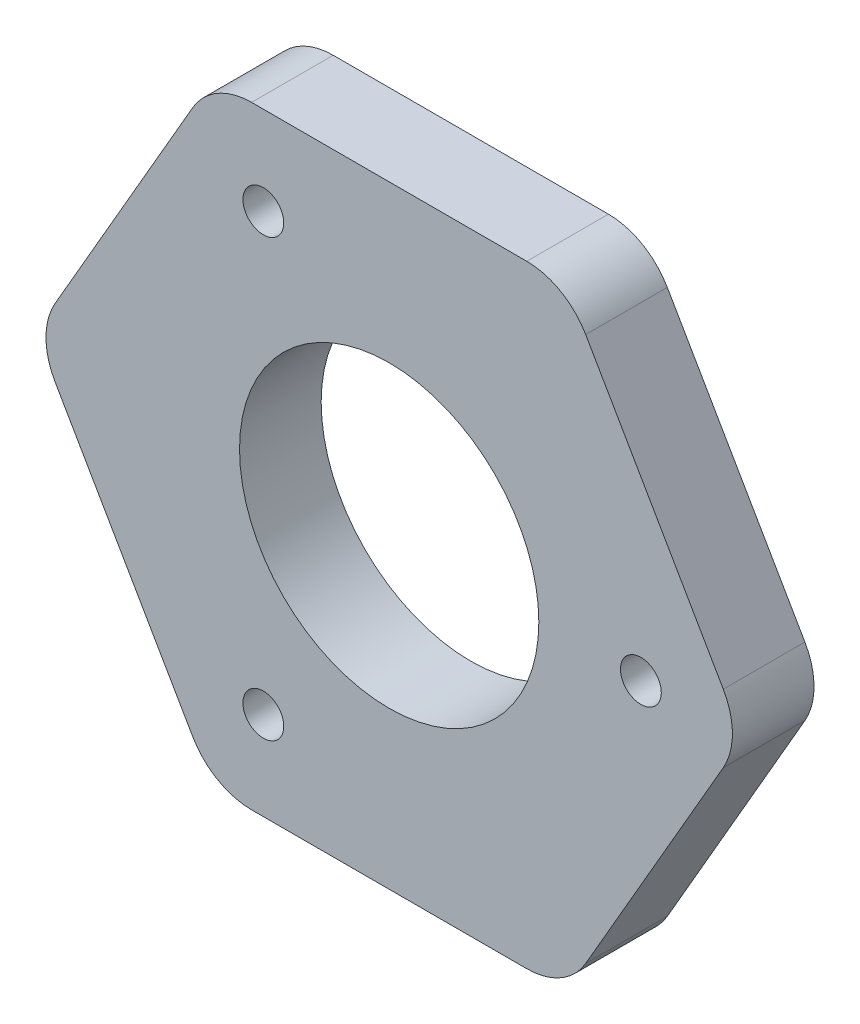
SolidWorks part; units mm, degrees
ref_plane "Front Plane" through (0, 0, 0) normal (0, 0, 1) x (1, 0, 0)
ref_plane "Top Plane" through (0, 0, 0) normal (0, 1, 0) x (1, 0, 0)
ref_plane "Right Plane" through (0, 0, 0) normal (1, 0, 0) x (0, 0, -1)
sketch "Sketch1" plane through (0, 0, 0) normal (0, 0, 1) x (1, 0, 0)
  line L6 (-32.5443, 48.7733) -> (-22.4311, 66.29)
  line L7 (-22.4311, 71.29) -> (-32.5443, 88.8067)
  line L8 (-36.8745, 91.3067) -> (-57.101, 91.3067)
  line L9 (-61.4311, 88.8067) -> (-71.5443, 71.29)
  line L10 (-71.5443, 66.29) -> (-61.4311, 48.7733)
  line L11 (-57.101, 46.2733) -> (-36.8745, 46.2733)
  circle A10 centre (-56.2377, 84.8115) radius 1.5
  circle A11 centre (-28.4877, 68.79) radius 1.5
  circle A12 centre (-46.9877, 68.79) radius 11
  circle A13 centre (-56.2377, 52.7685) radius 1.5
  arc A14 (-36.8745, 46.2733) -> (-32.5443, 48.7733) centre (-36.8745, 51.2733) ccw
  arc A15 (-22.4311, 66.29) -> (-22.4311, 71.29) centre (-26.7612, 68.79) ccw
  arc A16 (-32.5443, 88.8067) -> (-36.8745, 91.3067) centre (-36.8745, 86.3067) ccw
  arc A17 (-57.101, 91.3067) -> (-61.4311, 88.8067) centre (-57.101, 86.3067) ccw
  arc A18 (-71.5443, 71.29) -> (-71.5443, 66.29) centre (-67.2142, 68.79) ccw
  arc A19 (-61.4311, 48.7733) -> (-57.101, 46.2733) centre (-57.101, 51.2733) ccw
  dimension "D2" = 5
  dimension "D11" = 22
  dimension "D20" = 3
  dimension "D1" = 20.2265
  dimension "D3" = 60
  dimension "D4" = 60
  dimension "D5" = 60
  dimension "D6" = 60
  dimension "D7" = 60
  dimension "D8" = 32.0429
  dimension "D9" = 32.0429
  dimension "D10" = 32.0429
  dimension "D12" = 6.4952
  dimension "D13" = 6.4952
  dimension "D14" = 18.5
  dimension "D15" = 18.5
  dimension "D16" = 6.4952
  dimension "D17" = 46.2733
  dimension "D18" = 46.2733
  dimension "D19" = 36.8745
extrude "Boss-Extrude1" add sketch "Sketch1" along normal blind 6 separate body
